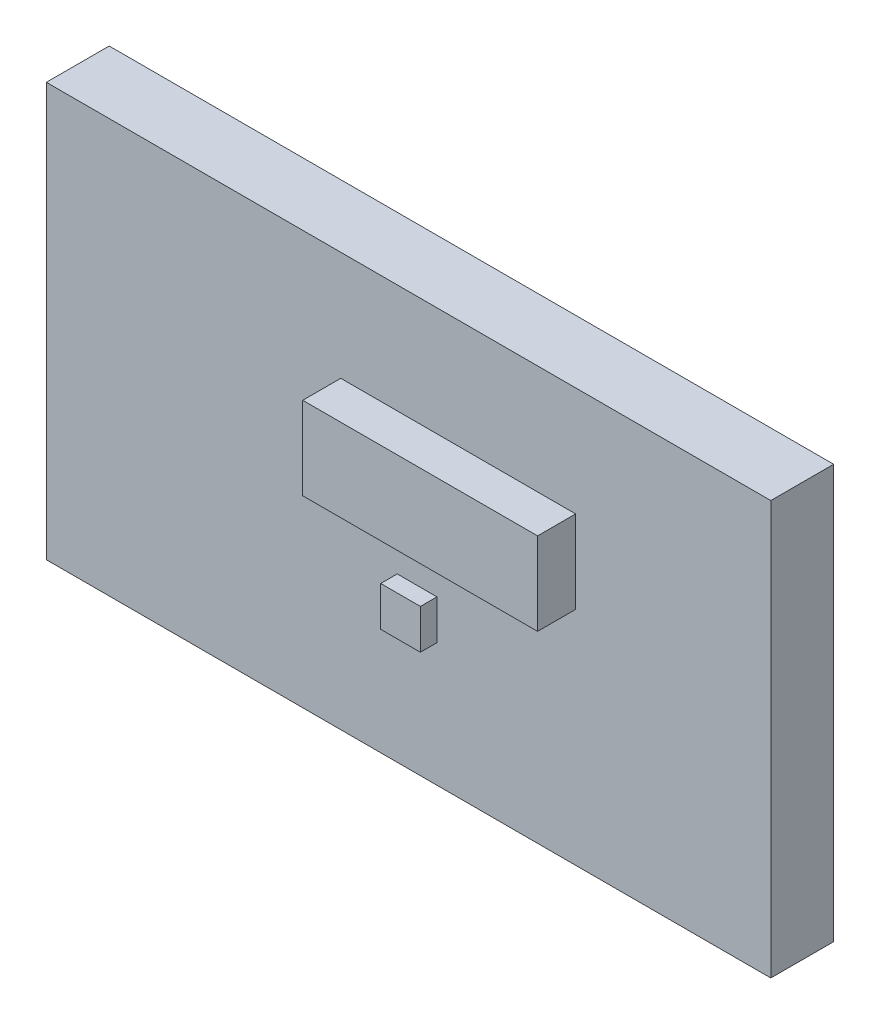
SolidWorks part; units mm, degrees
ref_plane "Plan de face" through (0, 0, 0) normal (0, 0, 1) x (1, 0, 0)
ref_plane "Plan de dessus" through (0, 0, 0) normal (0, 1, 0) x (1, 0, 0)
ref_plane "Plan de droite" through (0, 0, 0) normal (1, 0, 0) x (0, 0, -1)
sketch "Esquisse1" plane through (0, 0, 0) normal (0, 0, 1) x (1, 0, 0)
  line L1 (0, 0) -> (219, 0)
  line L2 (0, 0) -> (0, 125)
  line L3 (0, 125) -> (219, 125)
  line L4 (219, 0) -> (219, 125)
  point P4 (0, 0)
  dimension "D1" = 219
  dimension "D2" = 125
extrude "Boss.-Extru.1" add sketch "Esquisse1" along normal blind 19 contours L3 L4 L1 L2
sketch "Esquisse2" plane through (0, 0, 19) normal (0, 0, 1) x (1, 0, 0)
  line L1 (89, 92) -> (160, 92)
  line L2 (89, 92) -> (89, 67)
  line L3 (89, 67) -> (160, 67)
  line L4 (160, 92) -> (160, 67)
  line L5 (0, 0) -> (219, 0) construction
  line L6 (219, 0) -> (219, 125) construction
  dimension "D1" = 67
  dimension "D2" = 25
  dimension "D3" = 71
  dimension "D4" = 59
extrude "Boss.-Extru.2" add sketch "Esquisse2" along normal blind 11.5
sketch "Esquisse3" plane through (0, 0, 19) normal (0, 0, 1) x (1, 0, 0)
  line L1 (106.0733, 49.3221) -> (118.0733, 49.3221)
  line L2 (106.0733, 49.3221) -> (106.0733, 37.3221)
  line L3 (106.0733, 37.3221) -> (118.0733, 37.3221)
  line L4 (118.0733, 49.3221) -> (118.0733, 37.3221)
  dimension "D1" = 12
  dimension "D2" = 12
extrude "Boss.-Extru.3" add sketch "Esquisse3" along normal blind 5
